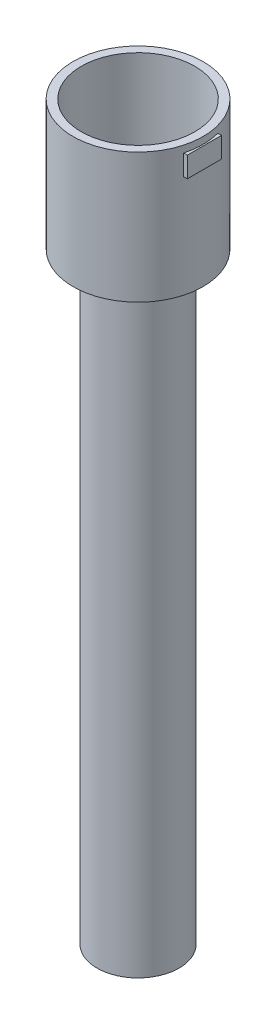
SolidWorks part; units mm, degrees
ref_plane "前视基准面" through (0, 0, 0) normal (0, 0, 1) x (1, 0, 0)
ref_plane "上视基准面" through (0, 0, 0) normal (0, 1, 0) x (1, 0, 0)
ref_plane "右视基准面" through (0, 0, 0) normal (1, 0, 0) x (0, 0, -1)
other "Configuration Table"
sketch "草图1" plane through (0, 0, 0) normal (0, 0, 1) x (1, 0, 0)
  line L0 (0, 0) -> (6, 0)
  line L1 (6, 0) -> (6, 88)
  line L2 (6, 88) -> (9.5, 88)
  line L3 (9.5, 88) -> (9.5, 107)
  line L4 (9.5, 107) -> (8.3, 107)
  line L5 (8.3, 107) -> (8.3, 89)
  line L6 (8.3, 89) -> (0, 89)
  line L7 (0, 89) -> (0, 0)
  line L8 (0, 0) -> (0, 107) construction
  dimension "x1" = 6
  dimension "x3" = 9.5
  dimension "x5" = 8.3
  dimension "y2" = 88
  dimension "y4" = 107
  dimension "y6" = 89
  dimension "y8" = 107
revolve "Stepped_output_tube" add sketch "草图1" angle 360 about L8
ref_plane "Guide_key_plane" through (0, 0, -2.5) normal (0, 0, 1) x (1, 0, 0)
sketch "草图3" plane through (0, 0, -2.5) normal (0, 0, 1) x (1, 0, 0)
  line L0 (-9.7, 103) -> (9.7, 103)
  line L1 (9.7, 103) -> (9.7, 106)
  line L2 (9.7, 106) -> (-9.7, 106)
  line L3 (-9.7, 106) -> (-9.7, 103)
  dimension "x0" = 9.7
  dimension "x1" = 9.7
  dimension "y0" = 103
  dimension "y2" = 106
extrude "Output_key" add sketch "草图3" along normal blind 5
sketch "草图4" plane through (0, 107, 0) normal (0, 1, 0) x (1, 0, 0)
  circle A0 centre (0, 0) radius 8.3
  dimension "diameter" = 16.6
extrude "D16_clearance" cut sketch "草图4" against normal blind 18
